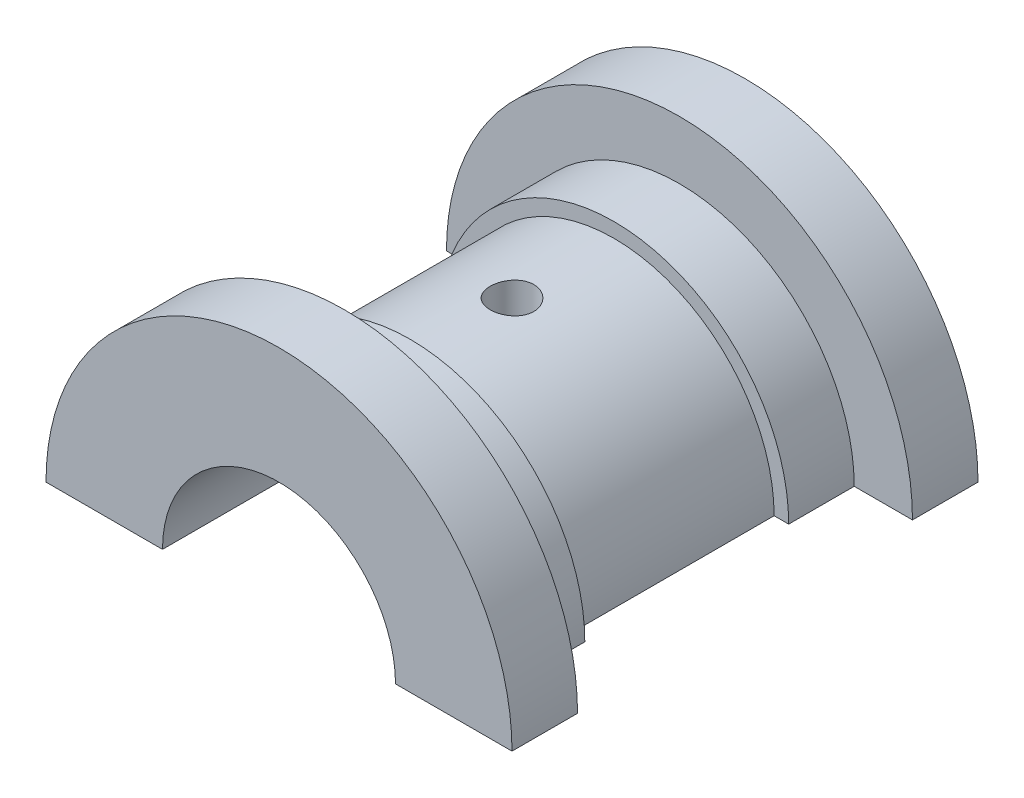
SolidWorks part; units mm, degrees
ref_plane "Front Plane" through (0, 0, 0) normal (0, 0, 1) x (1, 0, 0)
ref_plane "Top Plane" through (0, 0, 0) normal (0, 1, 0) x (1, 0, 0)
ref_plane "Right Plane" through (0, 0, 0) normal (1, 0, 0) x (0, 0, -1)
sketch "Sketch1" plane through (0, 0, 0) normal (0, 0, 1) x (1, 0, 0)
  circle A0 centre (0, 0) radius 16
  circle A2 centre (0, 0) radius 22
  dimension "D1" = 32
  dimension "D2" = 44
extrude "Boss-Extrude2" add sketch "Sketch1" along normal mid plane 14
sketch "Sketch3" plane through (0, 0, 7) normal (0, 0, 1) x (1, 0, 0)
  circle A3 centre (0, 0) radius 24
  dimension "D1" = 48
extrude "Boss-Extrude6" add sketch "Sketch3" along normal blind 9
sketch "Sketch6" plane through (0, 0, 16) normal (0, 0, 1) x (1, 0, 0)
  circle A0 centre (0, 0) radius 32
  dimension "64" = 64
extrude "Boss-Extrude7" add sketch "Sketch6" along normal blind 9
sketch "Sketch7" plane through (0, 0, -7) normal (0, 0, -1) x (-1, 0, 0)
  circle A0 centre (0, 0) radius 16 construction
  circle A3 centre (0, 0) radius 16
extrude "Cut-Extrude2" cut sketch "Sketch7" against normal through all
mirror "Mirror3" about plane through (0, 0, -7) normal (0, 0, 1) of bodies 120
sketch "Sketch8" plane through (0, 0, 25) normal (0, 0, 1) x (1, 0, 0)
  line L0 (-35.3721, 0) -> (34.5702, 0)
extrude "Cut-Extrude3" cut sketch "Sketch8" against normal through all flip side to cut
ref_plane "Plane1" through (0, 22, 0) normal (0, 1, 0) x (1, 0, 0)
sketch "Sketch9" plane through (0, 22, 0) normal (0, 1, 0) x (1, 0, 0)
  line L0 (-22, 7) -> (22, 7) construction
  line L1 (-22, 21) -> (-22, -7) construction
  line L2 (22, -7) -> (22, 21) construction
  circle A0 centre (0, 7) radius 4
  circle A1 centre (0, 7) radius 3
  dimension "D1" = 8
  dimension "D2" = 6
extrude "Cut-Extrude4" cut sketch "Sketch9" against normal through all contours A1
